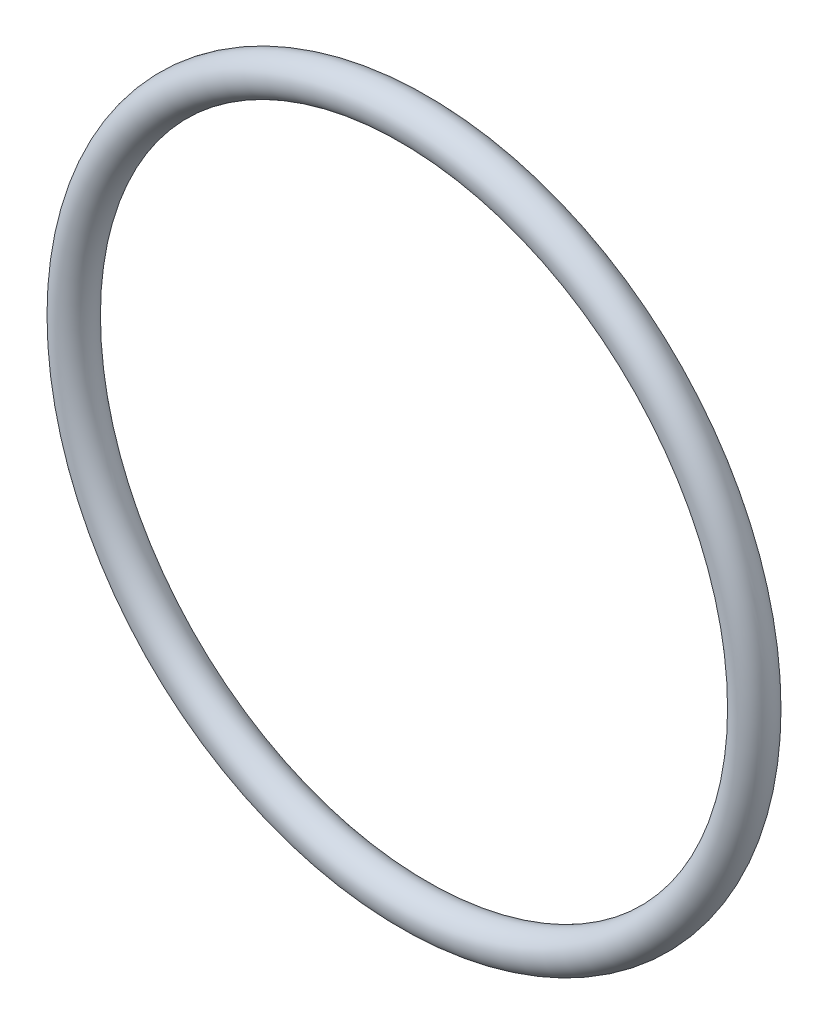
SolidWorks part; units mm, degrees
ref_plane "Front Plane" through (0, 0, 0) normal (0, 0, 1) x (1, 0, 0)
ref_plane "Top Plane" through (0, 0, 0) normal (0, 1, 0) x (1, 0, 0)
ref_plane "Right Plane" through (0, 0, 0) normal (1, 0, 0) x (0, 0, -1)
sketch "Sketch2" plane through (0, 0, 0) normal (0, 0, 1) x (1, 0, 0)
  circle A0 centre (900, 0) radius 900
  dimension "D1" = 1800
sketch "Sketch3" plane through (0, 0, 0) normal (0, 1, 0) x (1, 0, 0)
  circle A0 centre (0, 0) radius 50
  circle A1 centre (0, 0) radius 35
  dimension "D1" = 100
  dimension "D2" = 15
sweep "Sweep1" add profiles "Sketch3" path "Sketch2"
equation "\"hatchHoleDiameter\"= 600mm"
equation "\"hullThickness\"= 120mm"
equation "\"gasketHullInterconnectWidth\"= 100mm"
equation "\"collarThickness\"= 15"
equation "\"hatchTunnelLength\"=200"
equation "\"oRingDiameter\"=2"
equation "\"boltPatternRadiusInterconnect\"=500"
equation "\"interconnectBoltDiameter\"=30"
equation "\"hatchShaftDiameter\"=20"
equation "\"hatchMinima\"=50"
equation "\"hullDiameter\"=2000"
equation "\"hatchMaxima\"=180"
equation "\"bushingFlatHatch\"=15"
equation "\"hingePivotDiameter\"=20"
equation "\"handleWidth\"=250"
equation "\"handleHeight\"=160"
equation "\"handleThickness\"=25"
equation "\"FrameLength\"= 4300"
equation "\"FrameMidLength\"= 3000"
equation "\"TubeOD\"= 100"
equation "\"FrameBackFlat\"= 800"
equation "\"TubeWall\"=15"
equation "\"TopMemberAngle\"=120"
equation "\"FrameHight\"= 2500"
equation "\"D1@Sketch2\"=\"hullDiameter\" * .9"
equation "\"D1@Sketch3\"=\"TubeOD\""
